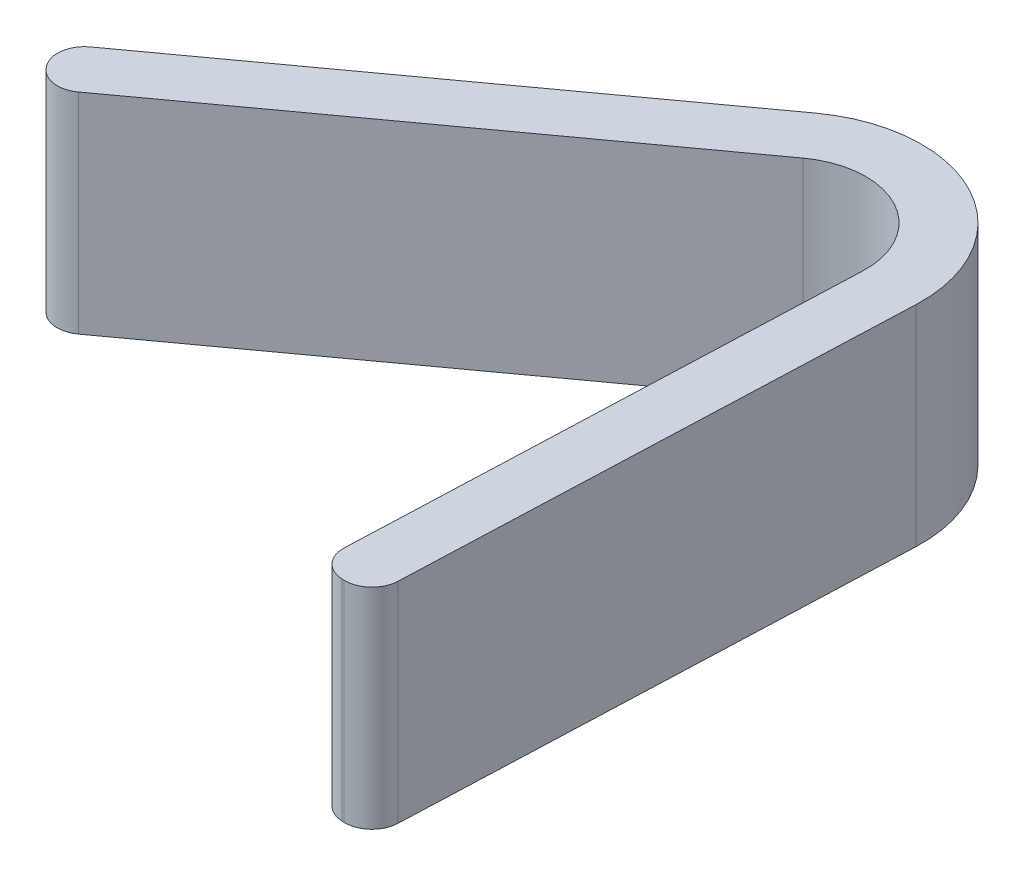
SolidWorks part; units mm, degrees
material "Titanium"
ref_plane "Front Plane" through (0, 0, 0) normal (0, 0, 1) x (1, 0, 0)
ref_plane "Top Plane" through (0, 0, 0) normal (0, 1, 0) x (1, 0, 0)
ref_plane "Right Plane" through (0, 0, 0) normal (1, 0, 0) x (0, 0, -1)
sketch "Sketch1" plane through (0, 0, 0) normal (0, 1, 0) x (1, 0, 0)
  line L0 (144.5459, -507.5488) -> (150.2877, -360.0272)
  line L1 (99.4939, -332.9006) -> (-31.0879, -427.8423)
  line L2 (159.9511, -320.3143) -> (118.3119, -358.7827) construction
  line L3 (150.2877, -360.0272) -> (118.3119, -358.7827) construction
  line L5 (118.3119, -358.7827) -> (56.2089, -492.2963) construction
  line L7 (75.2681, -321.8928) -> (118.3119, -358.7827) construction
  line L9 (144.5459, -507.5488) -> (144.2348, -515.5427)
  arc A0 (150.2877, -360.0272) -> (99.4939, -332.9006) centre (118.3119, -358.7827) ccw
  point P13 (235.224, -72.0996)
  dimension "D3" = 32
extrude "Extrude-Thin1" add sketch "Sketch1" against normal mid plane 62 thin thin type mid plane wall 16.5
fillet "Fillet1" radius 8 4 edges at (135.991, 0, 515.2218) (152.4786, 0, 515.8636) (-26.2364, 0, 434.515) (-35.9394, 0, 421.1696)
